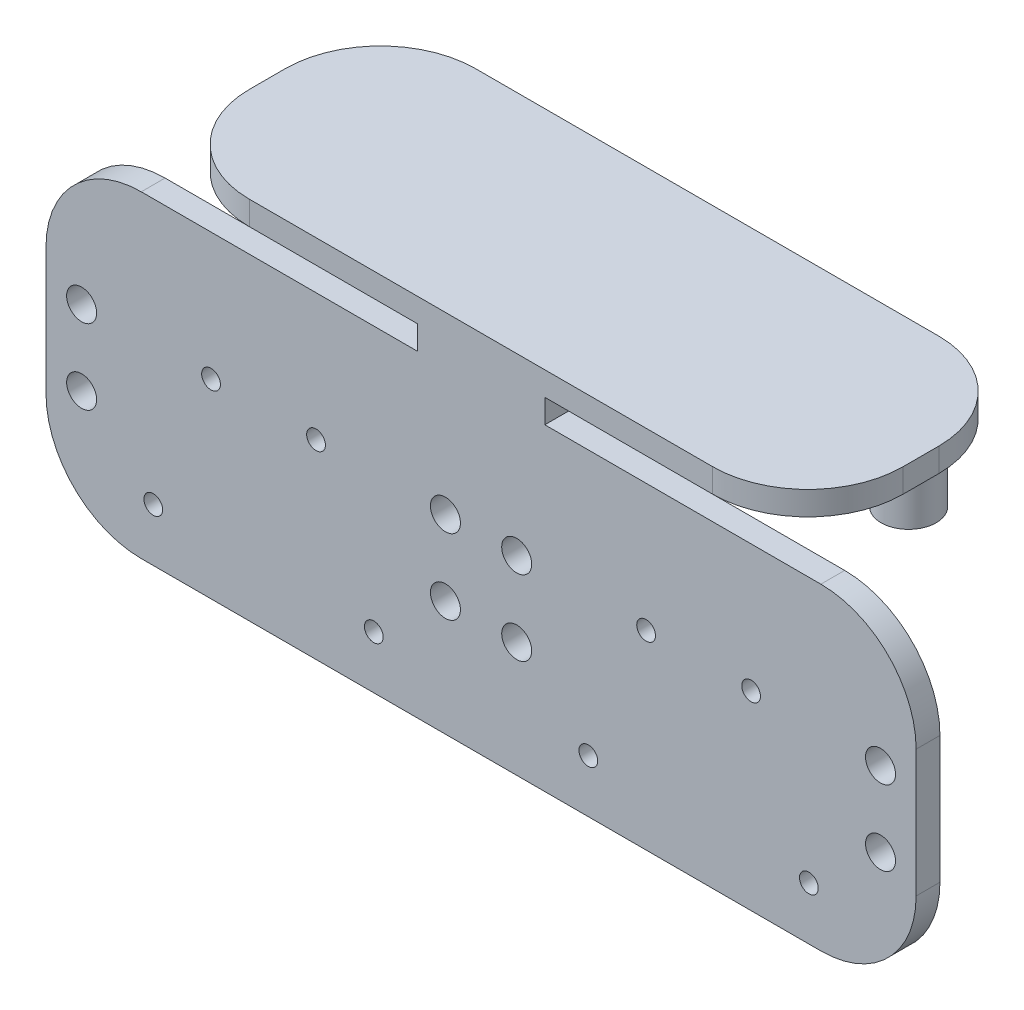
SolidWorks part; units mm, degrees
material "Plain Carbon Steel"
ref_plane "Front" through (0, 0, 0) normal (0, 0, 1) x (1, 0, 0)
ref_plane "Top" through (0, 0, 0) normal (0, 1, 0) x (1, 0, 0)
ref_plane "Right" through (0, 0, 0) normal (1, 0, 0) x (0, 0, -1)
ref_plane "Plane1" through (0, 0, 0) normal (0, 0, -1) x (-1, 0, 0)
sketch "Sketch1" plane through (0, 0, 0) normal (0, 0, -1) x (-1, 0, 0)
  line L0 (87, -37.5) -> (87, 11.1986)
  line L1 (87, 11.1986) -> (-29, 11.1986)
  line L2 (-29, 11.1986) -> (-29, -37.5)
  line L3 (-29, -37.5) -> (87, -37.5)
extrude "Boss-Extrude1" add sketch "Sketch1" against normal blind 3.175
sketch "Sketch2" plane through (0, 0, 3.175) normal (0, 0, 1) x (1, 0, 0)
  line L0 (14.5688, 11.1986) -> (14.5688, 4.8486)
  line L1 (14.5688, 4.8486) -> (29, 4.8486)
  line L2 (29, 4.8486) -> (29, 11.1986)
  line L3 (29, 11.1986) -> (14.5688, 11.1986)
extrude "Cut-Extrude1" cut sketch "Sketch2" against normal through all
sketch "Sketch3" plane through (0, 0, 3.175) normal (0, 0, 1) x (1, 0, 0)
  line L0 (-72.5688, 4.8486) -> (-72.5688, 11.1986)
  line L1 (-72.5688, 11.1986) -> (-87, 11.1986)
  line L2 (-87, 11.1986) -> (-87, 4.8486)
  line L3 (-87, 4.8486) -> (-72.5688, 4.8486)
extrude "Cut-Extrude2" cut sketch "Sketch3" against normal through all
sketch "Sketch4" plane through (0, 0, 0) normal (0, 0, -1) x (-1, 0, 0)
  line L0 (-14.5688, 8.0236) -> (-14.5688, 11.1986)
  line L1 (-14.5688, 11.1986) -> (72.5688, 11.1986)
  line L2 (72.5688, 11.1986) -> (72.5688, 8.0236)
  line L3 (72.5688, 8.0236) -> (-14.5688, 8.0236)
extrude "Boss-Extrude2" add sketch "Sketch4" along normal blind 26.9748
ref_plane "Plane2" through (0, 0, -14.77) normal (0, 0, -1) x (-1, 0, 0)
sketch "Sketch5" plane through (0, 0, -14.77) normal (0, 0, -1) x (-1, 0, 0)
  line L0 (-13.7284, 1.6736) -> (-10.05, 1.6736)
  line L1 (-10.05, 1.6736) -> (-10.05, 8.0236)
  line L2 (-10.05, 8.0236) -> (-13.7284, 8.0236)
  line L3 (-13.7284, 8.0236) -> (-13.7284, 1.6736)
  line L4 (-10.05, 1.6736) -> (-10.05, 8.0236) construction
revolve "Revolve1" add sketch "Sketch5" angle 360 about L4
ref_plane "Plane3" through (0, 0, -14.97) normal (0, 0, -1) x (-1, 0, 0)
sketch "Sketch6" plane through (0, 0, -14.97) normal (0, 0, -1) x (-1, 0, 0)
  line L0 (64.3788, 1.6736) -> (68.05, 1.6736)
  line L1 (68.05, 1.6736) -> (68.05, 8.0236)
  line L2 (68.05, 8.0236) -> (64.3788, 8.0236)
  line L3 (64.3788, 8.0236) -> (64.3788, 1.6736)
  line L4 (68.05, 1.6736) -> (68.05, 8.0236) construction
revolve "Revolve2" add sketch "Sketch6" angle 360 about L4
hole_wizard "#2 Clearance Hole1" positions "Sketch8" profile "Sketch7" hole size "#2" standard "ANSI Inch"
sketch "Sketch8" plane through (0, 0, 0) normal (0, 0, -1) x (-1, 0, 0)
  point P0 (72.6997, -30.4497)
  point P1 (65, -12.13)
  point P2 (51, -12.13)
  point P3 (43.3003, -30.4497)
  point P4 (14.6997, -30.4497)
  point P5 (7, -12.13)
  point P6 (-7, -12.13)
  point P7 (-14.6997, -30.4497)
sketch "Sketch7" plane through (-72.6997, -30.4497, 0) normal (1, 0, 0) x (0, 1, 0)
  line L0 (0, 0) -> (0, 3.175)
  line L1 (0, 3.175) -> (1.25, 3.175)
  line L2 (1.25, 3.175) -> (1.25, 0)
  line L5 (1.25, 0) -> (0, 0)
  line L11 (0, -6.35) -> (0, 107.95) construction
  dimension "Thru Hole Dia." = 2.5
  dimension "Thru Hole Depth" = 3.175
hole_wizard "#6 Clearance Hole1" positions "Sketch10" profile "Sketch9" hole size "#6" standard "ANSI Inch"
sketch "Sketch10" plane through (0, 0, 0) normal (0, 0, -1) x (-1, 0, 0)
  point P0 (33.75, -22.13)
  point P1 (82.25, -12.13)
  point P2 (82.25, -22.13)
  point P3 (-24.25, -12.13)
  point P4 (24.25, -12.13)
  point P5 (24.25, -22.13)
  point P6 (33.75, -12.13)
  point P7 (-24.25, -22.13)
sketch "Sketch9" plane through (-33.75, -22.13, 0) normal (1, 0, 0) x (0, 1, 0)
  line L0 (0, 0) -> (0, 3.175)
  line L1 (0, 3.175) -> (2, 3.175)
  line L2 (2, 3.175) -> (2, 0)
  line L5 (2, 0) -> (0, 0)
  line L11 (0, -6.35) -> (0, 107.95) construction
  dimension "Thru Hole Dia." = 4
  dimension "Thru Hole Depth" = 3.175
sketch "Sketch11" plane through (0, 0, 0) normal (0, 0, -1) x (-1, 0, 0)
  line L1 (20.5, -7) -> (37.5, -7)
  line L2 (20.5, -7) -> (20.5, -3)
  line L3 (20.5, -3) -> (37.5, -3)
  line L4 (37.5, -7) -> (37.5, -3)
extrude "Boss-Extrude3" add sketch "Sketch11" along normal blind 5.715
sketch "Sketch12" plane through (0, -7, 0) normal (0, -1, 0) x (1, 0, 0)
  line L0 (-20.5, -5.715) -> (-20.5, 0) construction
  line L1 (-37.5, -5.715) -> (-20.5, -5.715)
  line L2 (-37.5, -5.715) -> (-37.5, -2)
  line L3 (-37.5, -2) -> (-20.5, -2)
  line L4 (-20.5, -5.715) -> (-20.5, -2)
  line L5 (-25, -2) -> (-20.5, -2) construction
extrude "Boss-Extrude4" add sketch "Sketch12" along normal blind 19.05
sketch "Sketch13" plane through (0, 0, -2) normal (0, 0, 1) x (1, 0, 0)
  circle A0 centre (-33.75, -12.13) radius 2
  circle A1 centre (-24.25, -12.13) radius 2
  circle A2 centre (-24.25, -22.13) radius 2
  circle A3 centre (-33.75, -22.13) radius 2
extrude "Cut-Extrude3" cut sketch "Sketch13" against normal through all
sketch "Sketch14" plane through (0, 0, 0) normal (0, 0, -1) x (-1, 0, 0)
  line L0 (-14.5688, 8.0236) -> (72.5688, 8.0236) construction
  line L1 (-14.5688, 4.8486) -> (20.5, 4.8486)
  line L2 (-14.5688, 4.8486) -> (-14.5688, 8.0236)
  line L3 (-14.5688, 8.0236) -> (20.5, 8.0236)
  line L4 (20.5, 4.8486) -> (20.5, 8.0236)
  line L5 (-14.5688, 8.0236) -> (72.5688, 8.0236) construction
  line L6 (72.5688, 4.8486) -> (37.5, 4.8486)
  line L7 (72.5688, 4.8486) -> (72.5688, 8.0236)
  line L8 (72.5688, 8.0236) -> (37.5, 8.0236)
  line L9 (37.5, 4.8486) -> (37.5, 8.0236)
  line L10 (20.5, -3) -> (20.5, -26.05) construction
  point P14 (16.3358, 4.8486)
extrude "Cut-Extrude4" cut sketch "Sketch14" against normal up to surface (3.175 mm away) up to face at (-35.75, -22.13, 3.175)
fillet "Fillet1" radius 12.7 8 edges at (29, 4.8486, 1.5875) (29, -37.5, 1.5875) (-87, 4.8486, 1.5875) (-87, -37.5, 1.5875) (14.5688, 9.6111, 3.175) (-72.5688, 9.6111, 3.175) (14.5688, 9.6111, -26.9748) (-72.5688, 9.6111, -26.9748)
